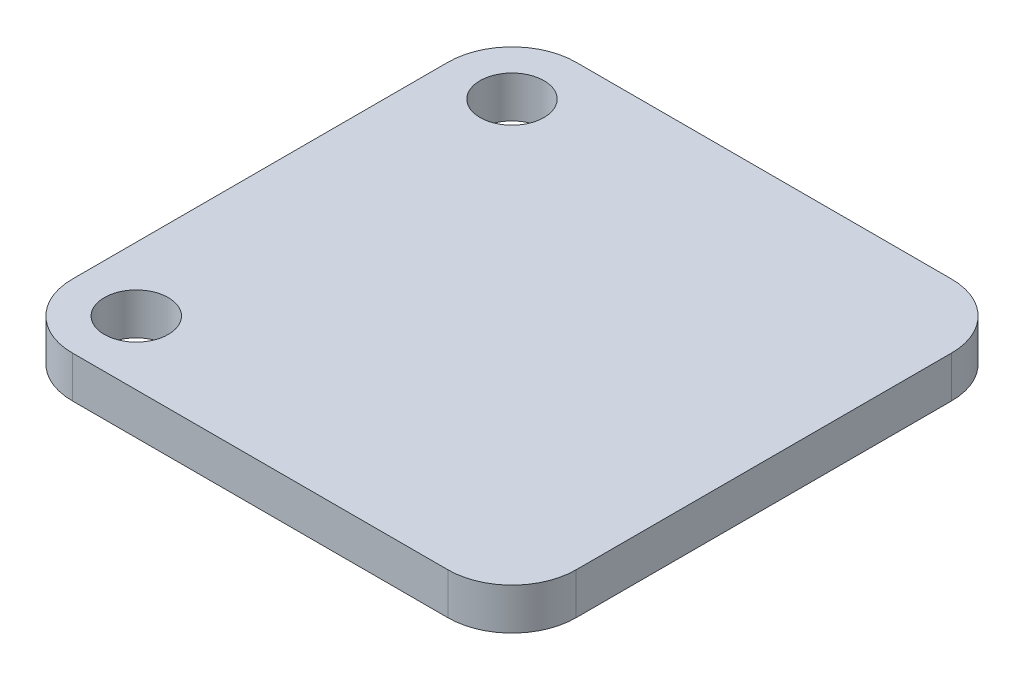
SolidWorks part; units mm, degrees
ref_plane "Front Plane" through (0, 0, 0) normal (0, 0, 1) x (1, 0, 0)
ref_plane "Top Plane" through (0, 0, 0) normal (0, 1, 0) x (1, 0, 0)
ref_plane "Right Plane" through (0, 0, 0) normal (1, 0, 0) x (0, 0, -1)
sketch "Sketch2" plane through (0, 0, 0) normal (0, 1, 0) x (1, 0, 0)
  line L1 (10, 10) -> (-10, 10)
  line L2 (10, 10) -> (10, -10)
  line L3 (10, -10) -> (-10, -10)
  line L4 (-10, 10) -> (-10, -10)
  line L5 (10, 10) -> (-10, -10) construction
  line L6 (10, -10) -> (-10, 10) construction
  point P0 (0, 0)
  dimension "D1" = 20
  dimension "D2" = 20
extrude "Boss-Extrude1" add sketch "Sketch2" along normal blind 1.65
fillet "Fillet1" radius 2.54 4 edges at (-10, 0.825, -10) (10, 0.825, -10) (-10, 0.825, 10) (10, 0.825, 10)
sketch "Sketch3" plane through (0, 1.65, 0) normal (0, 1, 0) x (1, 0, 0)
  line L12 (7.46, 7.46) -> (-7.46, 7.46)
  line L13 (-7.46, 7.46) -> (-7.46, -7.46)
  line L14 (-7.46, -7.46) -> (7.46, -7.46)
  line L15 (7.46, -7.46) -> (7.46, 7.46)
  line L19 (7.46, -7.46) -> (7.46, 7.46)
  circle A8 centre (-7.46, 7.46) radius 1.27
  circle A9 centre (-7.46, -7.46) radius 1.27
  dimension "D2" = 2.54
  dimension "D3" = 2.54
  dimension "D1" = 2.54
extrude "Cut-Extrude1" cut sketch "Sketch3" against normal through all contours A8 | A9
